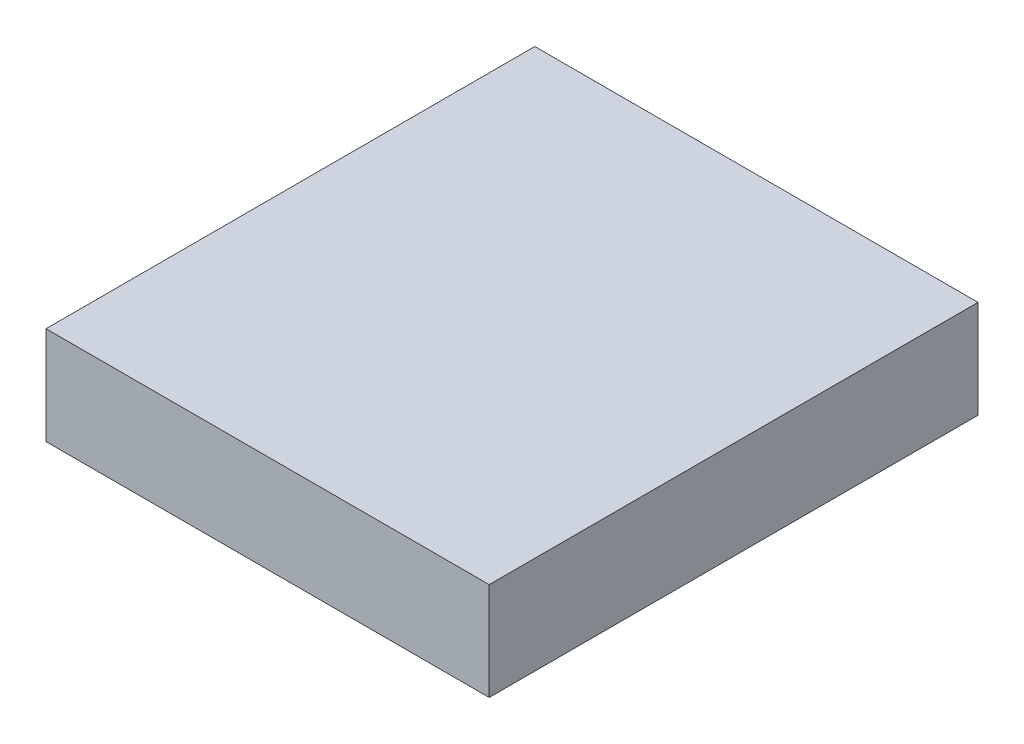
SolidWorks part; units mm, degrees
ref_plane "Front Plane" through (0, 0, 0) normal (0, 0, 1) x (1, 0, 0)
ref_plane "Top Plane" through (0, 0, 0) normal (0, 1, 0) x (1, 0, 0)
ref_plane "Right Plane" through (0, 0, 0) normal (1, 0, 0) x (0, 0, -1)
sketch "Sketch1" plane through (0, 0, 0) normal (0, 1, 0) x (1, 0, 0)
  line L1 (25.908, 28.575) -> (-25.908, 28.575)
  line L2 (25.908, 28.575) -> (25.908, -28.575)
  line L3 (25.908, -28.575) -> (-25.908, -28.575)
  line L4 (-25.908, 28.575) -> (-25.908, -28.575)
  line L5 (25.908, 28.575) -> (-25.908, -28.575) construction
  line L6 (25.908, -28.575) -> (-25.908, 28.575) construction
  point P0 (0, 0)
  dimension "D1" = 57.15
  dimension "D2" = 51.816
extrude "Boss-Extrude1" add sketch "Sketch1" along normal blind 11.43
